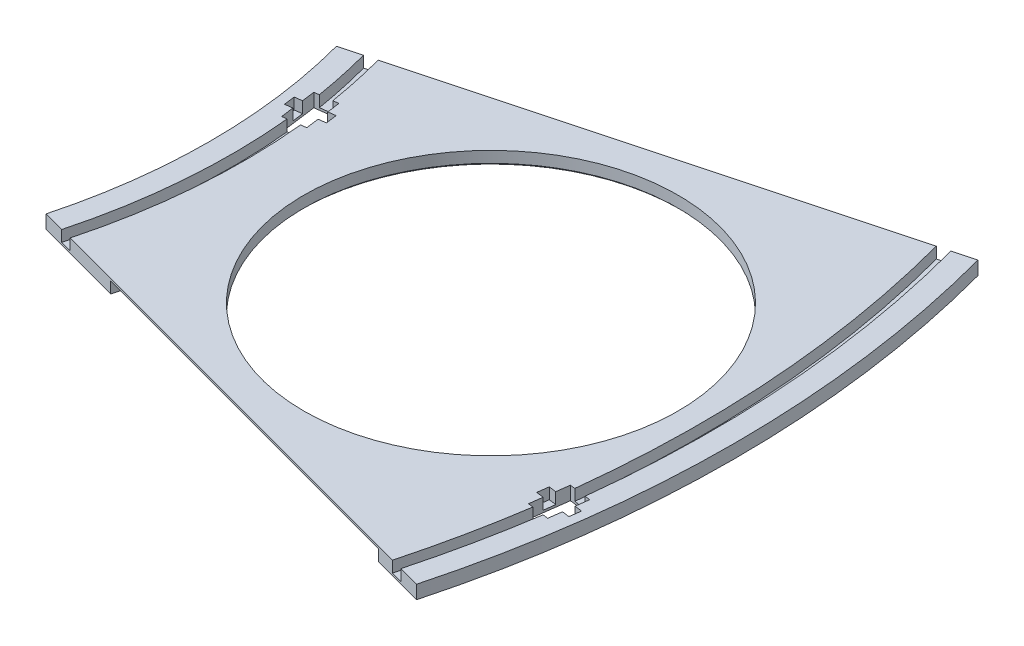
SolidWorks part; units mm, degrees
ref_plane "Ebene vorne" through (0, 0, 0) normal (0, 0, 1) x (1, 0, 0)
ref_plane "Ebene oben" through (0, 0, 0) normal (0, 1, 0) x (1, 0, 0)
ref_plane "Ebene rechts" through (0, 0, 0) normal (1, 0, 0) x (0, 0, -1)
sketch "Skizze1" plane through (0, 0, 0) normal (0, 1, 0) x (1, 0, 0)
  line L0 (0, 0) -> (290, 0) construction
  line L1 (280.1185, 75.0575) -> (144.8889, 38.8229)
  line L2 (144.8889, -38.8229) -> (280.1185, -75.0575)
  line L3 (0, 0) -> (280.1185, 75.0575) construction
  line L4 (0, 0) -> (280.1185, -75.0575) construction
  arc A0 (144.8889, -38.8229) -> (144.8889, 38.8229) centre (0, 0) ccw
  arc A1 (280.1185, -75.0575) -> (280.1185, 75.0575) centre (0, 0) ccw
  arc A2 (217.3333, -58.2343) -> (217.3333, 58.2343) centre (0, 0) ccw construction
  circle A3 centre (225, 0) radius 50
  dimension "D1" = 290
  dimension "D2" = 150
  dimension "D3" = 225
  dimension "D4" = 100
  dimension "D5" = 15
  dimension "D6" = 15
extrude "Aufsatz-Linear austragen1" add sketch "Skizze1" along normal blind 3.6
sketch "Skizze2" plane through (0, 3.6, 0) normal (0, 1, 0) x (1, 0, 0)
  line L0 (144.8889, -38.8229) -> (280.1185, -75.0575) construction
  line L1 (280.1185, 75.0575) -> (144.8889, 38.8229) construction
  line L2 (150.5878, 40.3499) -> (153.6788, 41.1781)
  line L3 (271.3286, 72.7023) -> (274.4195, 73.5305)
  line L4 (271.3286, -72.7023) -> (274.4195, -73.5305)
  line L5 (150.5878, -40.3499) -> (153.6788, -41.1781)
  arc A0 (150.5878, -40.3499) -> (150.5878, 40.3499) centre (0, 0) ccw
  arc A1 (153.6788, -41.1781) -> (153.6788, 41.1781) centre (0, 0) ccw
  arc A2 (271.3286, -72.7023) -> (271.3286, 72.7023) centre (0, 0) ccw
  arc A3 (274.4195, -73.5305) -> (274.4195, 73.5305) centre (0, 0) ccw
  dimension "D4" = 5.9
  dimension "D1" = 5.9
  dimension "D2" = 3.2
  dimension "D3" = 3.2
extrude "Schnitt-Linear austragen1" cut sketch "Skizze2" against normal blind 3
sketch "Skizze3" plane through (0, 3.6, 0) normal (0, 1, 0) x (1, 0, 0)
  line L0 (153.6788, -41.1781) -> (271.3286, -72.7023) construction
  line L1 (271.3286, 72.7023) -> (153.6788, 41.1781) construction
  line L2 (0, 0) -> (156.1526, 20.5579) construction
  line L3 (0, 0) -> (290, 0) construction
  line L4 (0, 0) -> (280.0832, -36.8736) construction
  line L5 (152.5256, 25.1235) -> (158.4743, 25.9067)
  line L6 (158.4743, 25.9067) -> (159.7795, 15.9922)
  line L7 (159.7795, 15.9922) -> (153.8309, 15.2091)
  line L8 (153.8309, 15.2091) -> (152.5256, 25.1235)
  line L9 (153.8309, 15.2091) -> (158.4743, 25.9067) construction
  line L10 (276.4562, -41.4393) -> (282.4049, -42.2225)
  line L11 (282.4049, -42.2225) -> (283.7101, -32.308)
  line L12 (283.7101, -32.308) -> (277.7615, -31.5248)
  line L13 (277.7615, -31.5248) -> (276.4562, -41.4393)
  line L14 (276.4562, -41.4393) -> (283.7101, -32.308) construction
  arc A0 (152.1333, -40.764) -> (152.1333, 40.764) centre (0, 0) ccw construction
  arc A1 (272.874, -73.1164) -> (272.874, 73.1164) centre (0, 0) ccw construction
  arc A2 (280.1185, -75.0575) -> (280.1185, 75.0575) centre (0, 0) ccw construction
  point P18 (156.1526, 20.5579)
  point P23 (280.0832, -36.8736)
  dimension "D1" = 157.5
  dimension "D2" = 282.5
  dimension "D3" = 7.5
  dimension "D4" = 7.5
  dimension "D5" = 10
  dimension "D6" = 6
extrude "Schnitt-Linear austragen2" cut sketch "Skizze3" against normal through all
sketch "Skizze4" plane through (0, 3.6, 0) normal (0, 1, 0) x (1, 0, 0)
  line L0 (150.9996, 21.3924) -> (160.914, 22.6977)
  line L1 (160.914, 22.6977) -> (161.3056, 19.7233)
  line L2 (161.3056, 19.7233) -> (151.3911, 18.4181)
  line L3 (151.3911, 18.4181) -> (150.9996, 21.3924)
  line L4 (275.3217, -34.7339) -> (285.2362, -36.0391)
  line L5 (285.2362, -36.0391) -> (284.8446, -39.0134)
  line L6 (284.8446, -39.0134) -> (274.9302, -37.7082)
  line L7 (274.9302, -37.7082) -> (275.3217, -34.7339)
  line L8 (153.8341, 25.2958) -> (152.5256, 25.1235) construction
  line L9 (152.5256, 25.1235) -> (153.8309, 15.2091) construction
  line L10 (277.7615, -31.5248) -> (276.4562, -41.4393) construction
  line L11 (282.2785, -32.1195) -> (279.1054, -31.7018) construction
  line L12 (151.3911, 18.4181) -> (160.914, 22.6977) construction
  line L13 (153.8309, 15.2091) -> (158.4743, 25.9067) construction
  line L14 (276.4562, -41.4393) -> (283.7101, -32.308) construction
  line L15 (276.4562, -41.4393) -> (277.8001, -41.6162) construction
  line L16 (275.3217, -34.7339) -> (284.8446, -39.0134) construction
  point P20 (156.1526, 20.5579)
  point P21 (156.1526, 20.5579)
  point P27 (280.0832, -36.8736)
  point P28 (280.0832, -36.8736)
  dimension "D1" = 10
  dimension "D2" = 3
extrude "Schnitt-Linear austragen3" cut sketch "Skizze4" against normal blind 3
chamfer "Fase1" distance 0.6 angle 45 1 edges at (225, 0, 50)
sketch "Skizze5" plane through (0, 0, 0) normal (0, -1, 0) x (1, 0, 0)
  line L0 (280.1185, -75.0575) -> (144.8889, -38.8229) construction
  line L1 (144.8889, 38.8229) -> (280.1185, 75.0575) construction
  line L2 (168.4575, 45.138) -> (266.2092, 71.3305)
  line L3 (266.2092, 71.3305) -> (268.0209, 64.569)
  line L4 (268.0209, 64.569) -> (170.2692, 38.3766)
  line L5 (170.2692, 38.3766) -> (168.4575, 45.138)
  line L6 (168.4575, -45.138) -> (266.2092, -71.3305)
  line L7 (266.2092, -71.3305) -> (268.0209, -64.569)
  line L8 (268.0209, -64.569) -> (170.2692, -38.3766)
  line L9 (170.2692, -38.3766) -> (168.4575, -45.138)
  arc A0 (266.2092, -71.3305) -> (266.2092, 71.3305) centre (0, 0) ccw construction
  circle A1 centre (225, 0) radius 50.6 construction
  arc A2 (144.8889, -38.8229) -> (144.8889, 38.8229) centre (0, 0) ccw construction
  arc A3 (144.8889, -38.8229) -> (144.8889, 38.8229) centre (0, 0) ccw construction
  arc A4 (168.4575, -45.138) -> (168.4575, 45.138) centre (0, 0) ccw construction
  dimension "D1" = 7
extrude "Schnitt-Linear austragen4" cut sketch "Skizze5" against normal through all
sketch "Skizze6" plane through (168.4575, 0, 45.138) normal (0.9659, 0, 0.2588) x (0.2588, 0, -0.9659)
  line L4 (0, 3.6) -> (7, 3.6)
  line L5 (7, 3.6) -> (7, 0)
  line L6 (7, 3.6) -> (7, 0) construction
  line L7 (7, 0) -> (0, 3)
  line L8 (0, 3.6) -> (0, 0) construction
  line L9 (0, 3) -> (0, 3.6)
  dimension "D1" = 3
extrude "Aufsatz-Linear austragen4" add sketch "Skizze6" along normal up to surface (101.2 mm away) up to face at (267.115, 1.8, 67.9498)
sketch "Skizze7" plane through (168.4575, 0, -45.138) normal (0.9659, 0, -0.2588) x (-0.2588, 0, -0.9659)
  line L0 (-7, 0) -> (-7, 3.6)
  line L1 (-7, 3.6) -> (0, 3.6)
  line L2 (0, 3.6) -> (0, 3)
  line L3 (0, 3.6) -> (0, 0) construction
  line L4 (0, 3) -> (-7, 0)
  dimension "D1" = 3
extrude "Aufsatz-Linear austragen5" add sketch "Skizze7" along normal up to surface (101.2 mm away) up to face at (267.115, 1.8, -67.9498)
equation "\"D6@Skizze1\"=\"D5@Skizze1\""
equation "\"D4@Skizze3\"=\"D3@Skizze3\""
